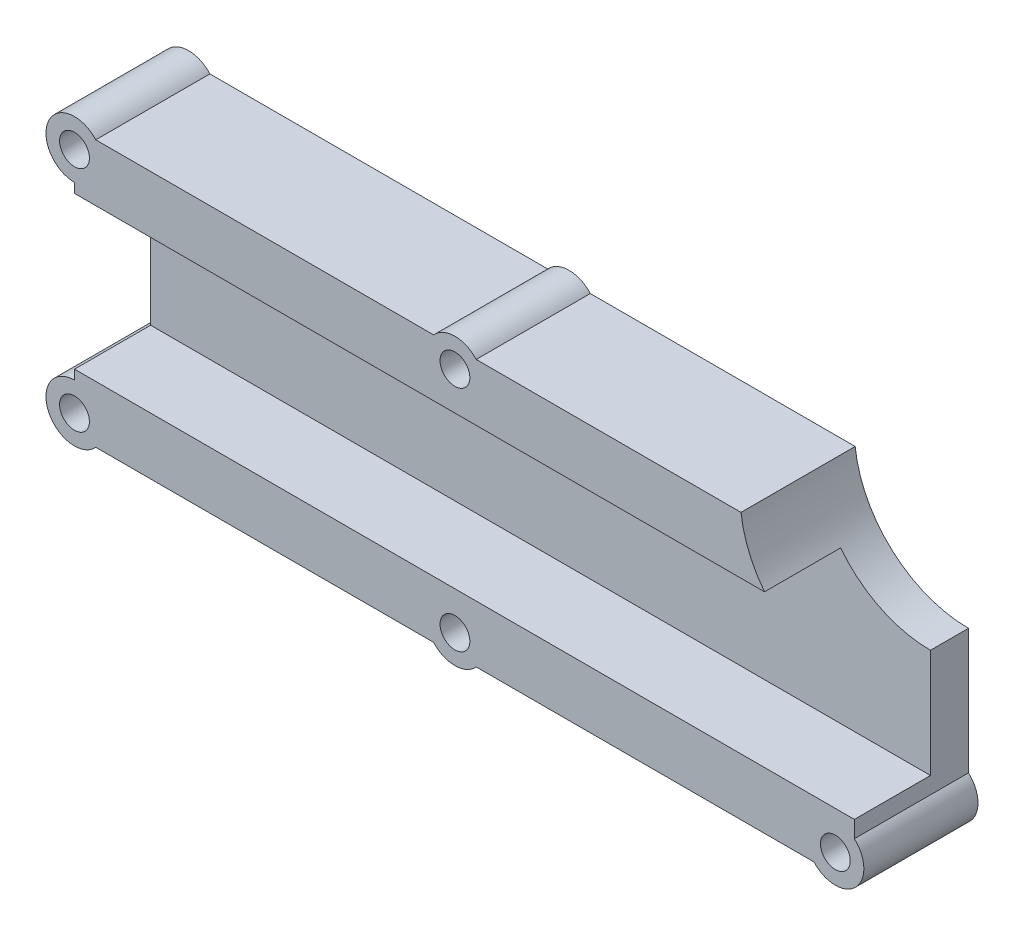
SolidWorks part; units mm, degrees
material "Nylon 101"
ref_plane "Front Plane" through (0, 0, 0) normal (0, 0, 1) x (1, 0, 0)
ref_plane "Top Plane" through (0, 0, 0) normal (0, 1, 0) x (1, 0, 0)
ref_plane "Right Plane" through (0, 0, 0) normal (1, 0, 0) x (0, 0, -1)
sketch "Sketch1" plane through (0, 0, 0) normal (0, 0, 1) x (1, 0, 0)
  line L0 (0, 38.1) -> (48.4056, 38.1) construction
  line L1 (3.5498, -3.175) -> (59.9502, -3.175)
  line L3 (3.5498, 41.275) -> (47.7551, 41.275)
  line L4 (66.675, 3.5498) -> (66.675, 24.4475)
  line L5 (63.5, 0) -> (63.5, 24.7139) construction
  line L6 (0, 0) -> (63.5, 0) construction
  line L8 (-3.175, 41.275) -> (66.675, 41.275) construction
  line L9 (-3.175, -3.175) -> (-3.175, 41.275) construction
  line L10 (-3.175, -3.175) -> (66.675, -3.175) construction
  line L11 (66.675, -3.175) -> (66.675, 41.275) construction
  line L12 (-3.5498, 41.275) -> (47.7551, 41.275)
  line L13 (0, 0) -> (-63.5, 0) construction
  line L15 (0, 38.1) -> (-63.5, 38.1) construction
  line L17 (-63.5, 4.7625) -> (-63.5, 33.3375)
  line L18 (-59.9502, -3.175) -> (-3.5498, -3.175)
  line L19 (47.7551, 41.275) -> (-59.9502, 41.275)
  line L20 (0, 0) -> (0, 38.1) construction
  line L22 (63.5, 0) -> (63.5, 38.1) construction
  line L24 (0, 38.1) -> (63.5, 38.1) construction
  circle A4 centre (0, 38.1) radius 2.4892
  circle A5 centre (0, 0) radius 2.4892
  circle A7 centre (63.5, 0) radius 2.4892
  arc A8 (3.5498, 41.275) -> (-3.5498, 41.275) centre (0, 38.1) ccw
  arc A9 (-3.5498, -3.175) -> (3.5498, -3.175) centre (0, 0) ccw
  arc A10 (59.9502, -3.175) -> (66.675, 3.5498) centre (63.5, 0) ccw
  circle A12 centre (-63.5, 38.1) radius 2.4892
  circle A14 centre (-63.5, 0) radius 2.4892
  arc A15 (-59.9502, 41.275) -> (-63.5, 33.3375) centre (-63.5, 38.1) ccw
  arc A16 (-63.5, 4.7625) -> (-59.9502, -3.175) centre (-63.5, 0) ccw
  arc A17 (47.7551, 41.275) -> (66.675, 24.4475) centre (66.675, 43.4975) ccw
  point P20 (-35.5701, 19.05)
  dimension "D3" = 4.9784
  dimension "D5" = 9.525
  dimension "D7" = 38.1
  dimension "D1" = 38.1
  dimension "D2" = 63.5
  dimension "D6" = 63.5
  dimension "D9" = 5.3975
  dimension "D4" = 3.175
extrude "Boss-Extrude1" add sketch "Sketch1" along normal blind 19.05
sketch "Sketch2" plane through (-63.5, 0, 0) normal (-1, 0, 0) x (0, 0, 1)
  line L0 (0, 4.7625) -> (0, 33.3375) construction
  line L16 (0, 31.75) -> (0, 6.35)
  line L17 (0, 6.35) -> (12.7, 6.35)
  line L18 (12.7, 6.35) -> (12.7, 31.75)
  line L19 (12.7, 31.75) -> (0, 31.75)
  point P3 (0, 19.05)
  point P9 (0, 19.05)
  dimension "D1" = 12.7
  dimension "D2" = 25.4
extrude "Cut-Extrude1" cut sketch "Sketch2" against normal through all
mirror "Mirror1" about plane through (0, 0, 19.05) normal (0, 0, 1) of bodies 103
delete or keep bodies "Body-Delete/Keep 1" type delete bodies bodies 103
